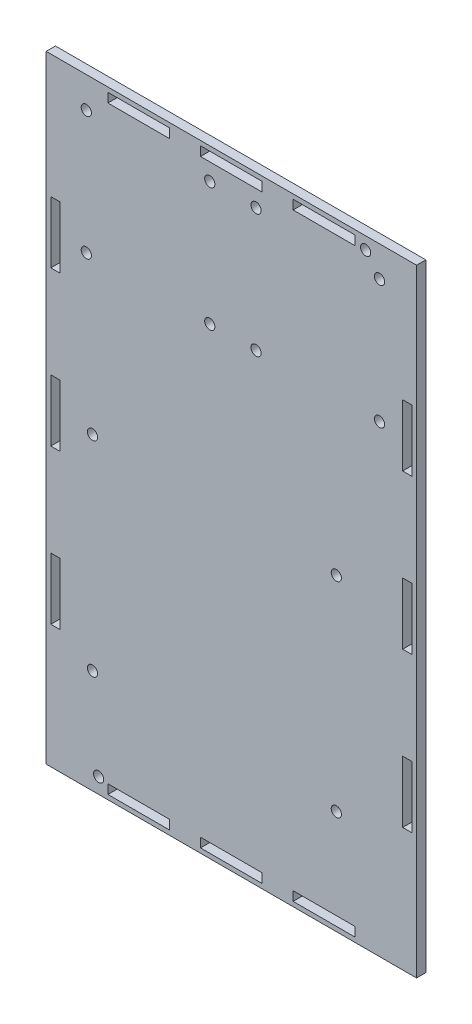
SolidWorks part; units mm, degrees
ref_plane "Front Plane" through (0, 0, 0) normal (0, 0, 1) x (1, 0, 0)
ref_plane "Top Plane" through (0, 0, 0) normal (0, 1, 0) x (1, 0, 0)
ref_plane "Right Plane" through (0, 0, 0) normal (1, 0, 0) x (0, 0, -1)
sketch "Sketch1" plane through (0, 0, 0) normal (0, 0, 1) x (1, 0, 0)
  line L0 (-68.4361, -170.2914) -> (-51.4361, -170.2914) construction
  line L1 (-68.4361, -175.2914) -> (51.5639, -175.2914)
  line L2 (-68.4361, -175.2914) -> (-68.4361, 24.7086)
  line L3 (-68.4361, 24.7086) -> (51.5639, 24.7086)
  line L4 (51.5639, -175.2914) -> (51.5639, 24.7086)
  line L17 (-51.4361, -170.2914) -> (-51.4361, -175.2914) construction
  line L18 (-51.4361, -170.2914) -> (-51.4361, 20.7086) construction
  line L19 (-51.4361, 20.7086) -> (35.0639, 20.7086) construction
  line L20 (-68.4361, 24.7086) -> (-65.4361, 24.7086) construction
  line L21 (-65.4361, 24.7086) -> (-65.4361, -175.2914) construction
  line L22 (-65.4361, 24.7086) -> (-65.4361, -25.2914) construction
  line L23 (-65.4361, -25.2914) -> (-65.4361, -75.2914) construction
  line L24 (-65.4361, -75.2914) -> (-65.4361, -125.2914) construction
  line L25 (-65.4361, -125.2914) -> (-65.4361, -175.2914) construction
  line L26 (51.5639, 24.7086) -> (48.5639, 24.7086) construction
  line L27 (-66.9361, -15.2914) -> (-63.9361, -15.2914)
  line L28 (-66.9361, -15.2914) -> (-66.9361, -35.2914)
  line L29 (-66.9361, -35.2914) -> (-63.9361, -35.2914)
  line L30 (-63.9361, -15.2914) -> (-63.9361, -35.2914)
  line L31 (-66.9361, -15.2914) -> (-63.9361, -35.2914) construction
  line L32 (-66.9361, -35.2914) -> (-63.9361, -15.2914) construction
  line L33 (-66.9361, -85.2914) -> (-63.9361, -85.2914)
  line L34 (-66.9361, -85.2914) -> (-66.9361, -65.2914)
  line L35 (-66.9361, -65.2914) -> (-63.9361, -65.2914)
  line L36 (-63.9361, -85.2914) -> (-63.9361, -65.2914)
  line L37 (-66.9361, -85.2914) -> (-63.9361, -65.2914) construction
  line L38 (-66.9361, -65.2914) -> (-63.9361, -85.2914) construction
  line L39 (-66.9361, -115.2914) -> (-63.9361, -115.2914)
  line L40 (-66.9361, -115.2914) -> (-66.9361, -135.2914)
  line L41 (-66.9361, -135.2914) -> (-63.9361, -135.2914)
  line L42 (-63.9361, -115.2914) -> (-63.9361, -135.2914)
  line L43 (-66.9361, -115.2914) -> (-63.9361, -135.2914) construction
  line L44 (-66.9361, -135.2914) -> (-63.9361, -115.2914) construction
  line L45 (48.5639, 24.7086) -> (48.5639, -25.2914) construction
  line L46 (48.5639, -25.2914) -> (48.5639, -75.2914) construction
  line L47 (48.5639, -75.2914) -> (48.5639, -125.2914) construction
  line L48 (48.5639, -125.2914) -> (48.5639, -175.2914) construction
  line L49 (-68.4361, -175.2914) -> (-68.4361, -172.2914) construction
  line L50 (47.0639, -15.2914) -> (50.0639, -15.2914)
  line L51 (47.0639, -15.2914) -> (47.0639, -35.2914)
  line L52 (47.0639, -35.2914) -> (50.0639, -35.2914)
  line L53 (50.0639, -15.2914) -> (50.0639, -35.2914)
  line L54 (47.0639, -15.2914) -> (50.0639, -35.2914) construction
  line L55 (47.0639, -35.2914) -> (50.0639, -15.2914) construction
  line L56 (47.0639, -65.2914) -> (50.0639, -65.2914)
  line L57 (47.0639, -65.2914) -> (47.0639, -85.2914)
  line L58 (47.0639, -85.2914) -> (50.0639, -85.2914)
  line L59 (50.0639, -65.2914) -> (50.0639, -85.2914)
  line L60 (47.0639, -65.2914) -> (50.0639, -85.2914) construction
  line L61 (47.0639, -85.2914) -> (50.0639, -65.2914) construction
  line L62 (47.0639, -115.2914) -> (50.0639, -115.2914)
  line L63 (47.0639, -115.2914) -> (47.0639, -135.2914)
  line L64 (47.0639, -135.2914) -> (50.0639, -135.2914)
  line L65 (50.0639, -115.2914) -> (50.0639, -135.2914)
  line L66 (47.0639, -115.2914) -> (50.0639, -135.2914) construction
  line L67 (47.0639, -135.2914) -> (50.0639, -115.2914) construction
  line L68 (-68.4361, -172.2914) -> (-38.4361, -172.2914) construction
  line L69 (-38.4361, -172.2914) -> (-8.4361, -172.2914) construction
  line L70 (-8.4361, -172.2914) -> (21.5639, -172.2914) construction
  line L71 (21.5639, -172.2914) -> (51.5639, -172.2914) construction
  line L72 (-68.4361, 24.7086) -> (-68.4361, 21.7086) construction
  line L73 (-48.4361, -173.7914) -> (-28.4361, -173.7914)
  line L74 (-48.4361, -173.7914) -> (-48.4361, -170.7914)
  line L75 (-48.4361, -170.7914) -> (-28.4361, -170.7914)
  line L76 (-28.4361, -173.7914) -> (-28.4361, -170.7914)
  line L77 (-48.4361, -173.7914) -> (-28.4361, -170.7914) construction
  line L78 (-48.4361, -170.7914) -> (-28.4361, -173.7914) construction
  line L79 (-18.4361, -170.7914) -> (1.5639, -170.7914)
  line L80 (-18.4361, -170.7914) -> (-18.4361, -173.7914)
  line L81 (-18.4361, -173.7914) -> (1.5639, -173.7914)
  line L82 (1.5639, -170.7914) -> (1.5639, -173.7914)
  line L83 (-18.4361, -170.7914) -> (1.5639, -173.7914) construction
  line L84 (-18.4361, -173.7914) -> (1.5639, -170.7914) construction
  line L85 (11.5639, -173.7914) -> (31.5639, -173.7914)
  line L86 (11.5639, -173.7914) -> (11.5639, -170.7914)
  line L87 (11.5639, -170.7914) -> (31.5639, -170.7914)
  line L88 (31.5639, -173.7914) -> (31.5639, -170.7914)
  line L89 (11.5639, -173.7914) -> (31.5639, -170.7914) construction
  line L90 (11.5639, -170.7914) -> (31.5639, -173.7914) construction
  line L91 (-68.4361, 21.7086) -> (-38.4361, 21.7086) construction
  line L92 (-38.4361, 21.7086) -> (-8.4361, 21.7086) construction
  line L93 (-8.4361, 21.7086) -> (21.5639, 21.7086) construction
  line L94 (21.5639, 21.7086) -> (51.5639, 21.7086) construction
  line L96 (-48.4361, 23.2086) -> (-28.4361, 23.2086)
  line L97 (-48.4361, 23.2086) -> (-48.4361, 20.2086)
  line L98 (-48.4361, 20.2086) -> (-28.4361, 20.2086)
  line L99 (-28.4361, 23.2086) -> (-28.4361, 20.2086)
  line L100 (-48.4361, 23.2086) -> (-28.4361, 20.2086) construction
  line L101 (-48.4361, 20.2086) -> (-28.4361, 23.2086) construction
  line L102 (-18.4361, 23.2086) -> (1.5639, 23.2086)
  line L103 (-18.4361, 23.2086) -> (-18.4361, 20.2086)
  line L104 (-18.4361, 20.2086) -> (1.5639, 20.2086)
  line L105 (1.5639, 23.2086) -> (1.5639, 20.2086)
  line L106 (-18.4361, 23.2086) -> (1.5639, 20.2086) construction
  line L107 (-18.4361, 20.2086) -> (1.5639, 23.2086) construction
  line L108 (11.5639, 23.2086) -> (31.5639, 23.2086)
  line L109 (11.5639, 23.2086) -> (11.5639, 20.2086)
  line L110 (11.5639, 20.2086) -> (31.5639, 20.2086)
  line L111 (31.5639, 23.2086) -> (31.5639, 20.2086)
  line L112 (11.5639, 23.2086) -> (31.5639, 20.2086) construction
  line L113 (11.5639, 20.2086) -> (31.5639, 23.2086) construction
  circle A0 centre (-55.4361, 14.7086) radius 1.65
  circle A1 centre (-15.4361, 14.7086) radius 1.65
  circle A2 centre (-15.4361, -25.2914) radius 1.65
  circle A3 centre (-55.4361, -25.2914) radius 1.65
  circle A4 centre (-0.4365, 14.8212) radius 1.65
  circle A5 centre (39.5635, 14.8212) radius 1.65
  circle A7 centre (39.5635, -25.1788) radius 1.65
  circle A8 centre (-0.4365, -25.1788) radius 1.65
  circle A9 centre (-53.4361, -75.2914) radius 1.65
  circle A10 centre (25.5639, -75.2914) radius 1.65
  circle A11 centre (25.5639, -141.5914) radius 1.65
  circle A12 centre (-53.4361, -141.5914) radius 1.65
  circle A13 centre (-51.4361, -170.2914) radius 1.65
  circle A14 centre (35.0639, 20.7086) radius 1.65
  point P0 (0, 0)
  point P5 (-50.4723, 24.7165)
  point P17 (2.0994, 24.7165)
  point P24 (-26.8582, -43.2074)
  dimension "D1" = 40
  dimension "D14" = 79
  dimension "D19" = 66.3
  dimension "D21" = 86.5
  dimension "D30" = 3
  dimension "D2" = 40
  dimension "D3" = 40
  dimension "D4" = 13
  dimension "D5" = 15
  dimension "D6" = 15
  dimension "D7" = 40
  dimension "D8" = 40
  dimension "D9" = 40
  dimension "D10" = 10
  dimension "D11" = 200
  dimension "D12" = 15
  dimension "D13" = 50
  dimension "D15" = 66.3
  dimension "D16" = 120
  dimension "D17" = 5
  dimension "D18" = 17
  dimension "D20" = 79
  dimension "D22" = 191
  dimension "D23" = 40
  dimension "D24" = 13
  dimension "D25" = 40
  dimension "D26" = 3
  dimension "D27" = 3
  dimension "D28" = 20
  dimension "D29" = 3
  dimension "D31" = 30
  dimension "D32" = 30
  dimension "D33" = 30
  dimension "D34" = 30
  dimension "D35" = 3
  dimension "D36" = 3
  dimension "D37" = 20
  dimension "D38" = 20
  dimension "D39" = 3
  dimension "D40" = 20
extrude "Boss-Extrude1" add sketch "Sketch1" along normal blind 3
